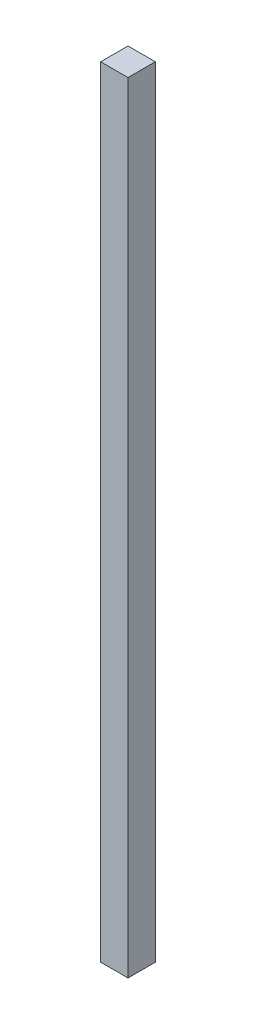
SolidWorks part; units mm, degrees
ref_plane "Ön Düzlem" through (0, 0, 0) normal (0, 0, 1) x (1, 0, 0)
ref_plane "Üst Düzlem" through (0, 0, 0) normal (0, 1, 0) x (1, 0, 0)
ref_plane "Sağ Düzlem" through (0, 0, 0) normal (1, 0, 0) x (0, 0, -1)
sketch "Sketch2" plane through (0, 0, 0) normal (0, 1, 0) x (1, 0, 0)
  line L1 (-24.5946, 16.2162) -> (45.4054, 16.2162)
  line L2 (-24.5946, 16.2162) -> (-24.5946, -53.7838)
  line L3 (-24.5946, -53.7838) -> (45.4054, -53.7838)
  line L4 (45.4054, 16.2162) -> (45.4054, -53.7838)
  dimension "D1" = 70
  dimension "D2" = 70
extrude "Boss-Extrude1" add sketch "Sketch2" along normal blind 2000
